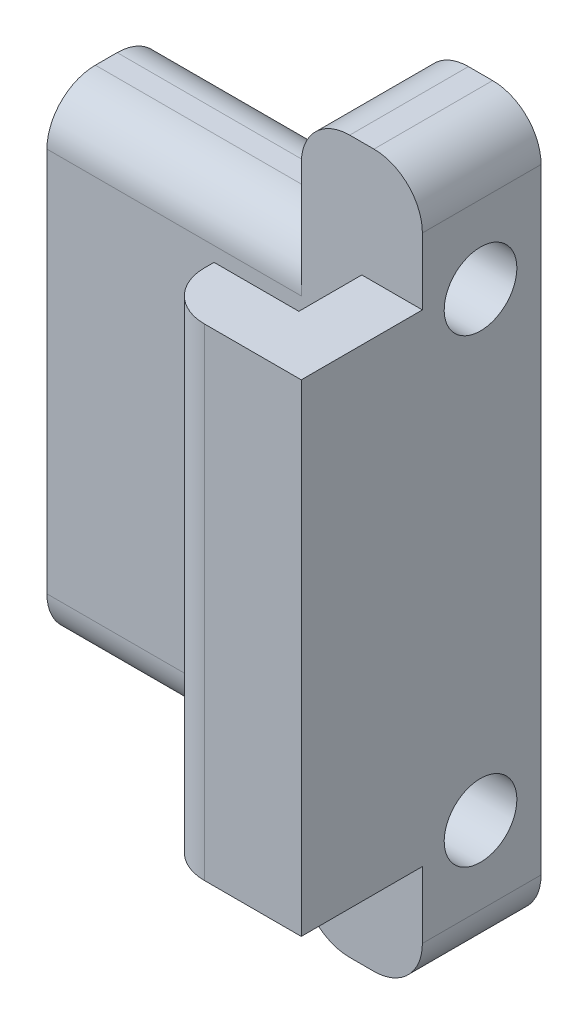
SolidWorks part; units mm, degrees
ref_plane "前视基准面" through (0, 0, 0) normal (0, 0, 1) x (1, 0, 0)
ref_plane "上视基准面" through (0, 0, 0) normal (0, 1, 0) x (1, 0, 0)
ref_plane "右视基准面" through (0, 0, 0) normal (1, 0, 0) x (0, 0, -1)
other "Configuration Table"
sketch "草图2" plane through (0, 0, 0) normal (0, 0, 1) x (1, 0, 0)
  line L0 (0, 0) -> (0, 19.9)
  line L1 (0, 19.9) -> (10.5, 19.9)
  line L2 (10.5, 19.9) -> (10.5, 24.65)
  line L3 (10.5, 24.65) -> (15.5, 24.65)
  line L4 (15.5, 24.65) -> (15.5, -4.75)
  line L5 (15.5, -4.75) -> (10.5, -4.75)
  line L6 (10.5, -4.75) -> (10.5, 0)
  line L7 (10.5, 0) -> (0, 0)
  dimension "D1" = 19.9
  dimension "D2" = 10.5
  dimension "D3" = 10.5
  dimension "D4" = 4.75
  dimension "D5" = 4.75
  dimension "D6" = 5
extrude "凸台-拉伸1" add sketch "草图2" along normal blind 4.9
fillet "圆角1" radius 2 4 edges at (5.25, 0, 4.9) (5.25, 0, 0) (5.25, 19.9, 0) (5.25, 19.9, 4.9)
sketch "草图3" plane through (15.5, 0, 0) normal (1, 0, 0) x (0, 0, -1)
  line L1 (0, 9.95) -> (-4.9, 9.95) construction
  line L2 (0, -4.75) -> (0, 24.65) construction
  line L3 (-4.9, -4.75) -> (-4.9, 24.65) construction
  circle A0 centre (-2.5, 19.45) radius 1.5
  circle A1 centre (-2.5, 0.45) radius 1.5
  dimension "D1" = 3
  dimension "D2" = 19
extrude "切除-拉伸1" cut sketch "草图3" against normal blind 3
sketch "草图4" plane through (0, 0, 4.9) normal (0, 0, 1) x (1, 0, 0)
  line L0 (15.5, -4.75) -> (15.5, 24.65) construction
  line L1 (10.5, 19.9) -> (15.5, 19.9)
  line L2 (10.5, 19.9) -> (10.5, 0)
  line L3 (10.5, 0) -> (15.5, 0)
  line L4 (15.5, 19.9) -> (15.5, 0)
extrude "凸台-拉伸2" add sketch "草图4" along normal blind 5
sketch "草图5" plane through (0, 19.9, 0) normal (0, 1, 0) x (1, 0, 0)
  line L1 (10.5, -4.9) -> (13, -4.9)
  line L2 (10.5, -4.9) -> (10.5, -7.5)
  line L3 (10.5, -7.5) -> (13, -7.5)
  line L4 (13, -4.9) -> (13, -7.5)
  dimension "D1" = 2.6
  dimension "D2" = 2.5
extrude "切除-拉伸2" cut sketch "草图5" against normal through all
fillet "圆角3" radius 2 4 edges at (15.5, -4.75, 2.45) (10.5, -4.75, 2.45) (10.5, 24.65, 2.45) (15.5, 24.65, 2.45)
sketch "草图6" plane through (10.5, 0, 0) normal (-1, 0, 0) x (0, 0, 1)
  line L1 (9.9, 19.9) -> (7.5, 19.9)
  line L2 (9.9, 19.9) -> (9.9, 0)
  line L3 (9.9, 0) -> (7.5, 0)
  line L4 (7.5, 19.9) -> (7.5, 0)
extrude "凸台-拉伸3" add sketch "草图6" along normal blind 1
fillet "圆角4" radius 2 1 edges at (9.5, 9.95, 9.9)
